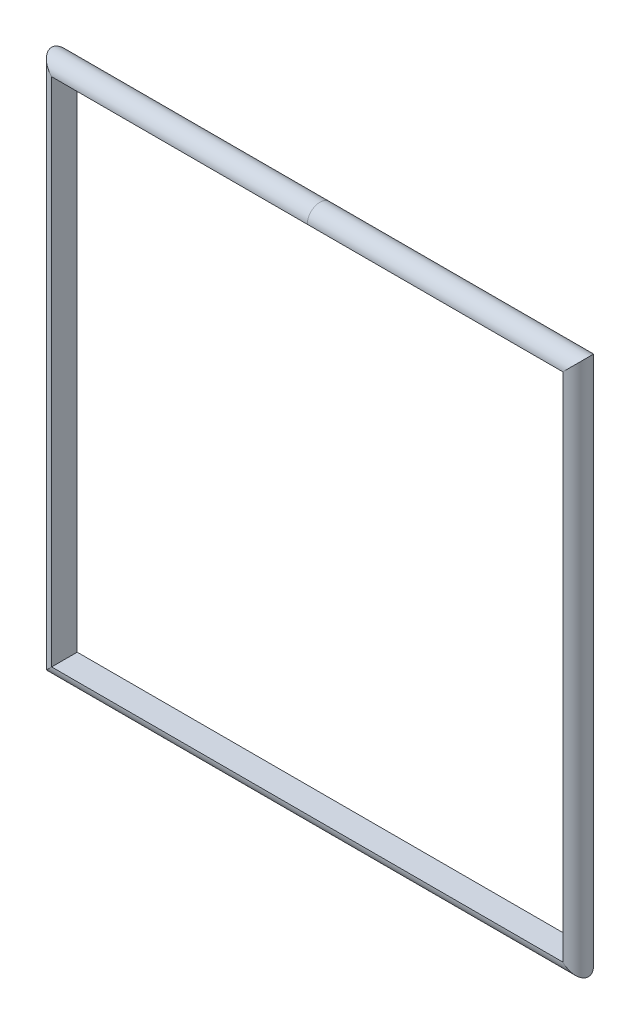
SolidWorks part; units mm, degrees
ref_plane "Front Plane" through (0, 0, 0) normal (0, 0, 1) x (1, 0, 0)
ref_plane "Top Plane" through (0, 0, 0) normal (0, 1, 0) x (1, 0, 0)
ref_plane "Right Plane" through (0, 0, 0) normal (1, 0, 0) x (0, 0, -1)
sketch "Sketch2" plane through (0, 0, 0) normal (0, 0, 1) x (1, 0, 0)
  line L2 (-0.3, -0.3) -> (0.3, -0.3)
  line L3 (-0.3, -0.3) -> (-0.3, 0.3)
  line L4 (-0.3, 0.3) -> (0.3, 0.3)
  line L5 (0.3, -0.3) -> (0.3, 0.3)
  line L6 (-0.3, -0.3) -> (0.3, 0.3) construction
  line L7 (-0.3, 0.3) -> (0.3, -0.3) construction
  point P0 (0, 0)
  dimension "D1" = 0.6
  dimension "D2" = 0.6
sketch "Sketch1" plane through (0, 0, 0) normal (1, 0, 0) x (0, 0, -1)
  line L0 (-0.015, 0.3) -> (0.015, 0.3)
  arc A0 (0.015, 0.3) -> (-0.015, 0.3) centre (0, 0.3) ccw
  dimension "D1" = 0.03
sweep "Sweep2" add profiles "Sketch1" path "Sketch2"
